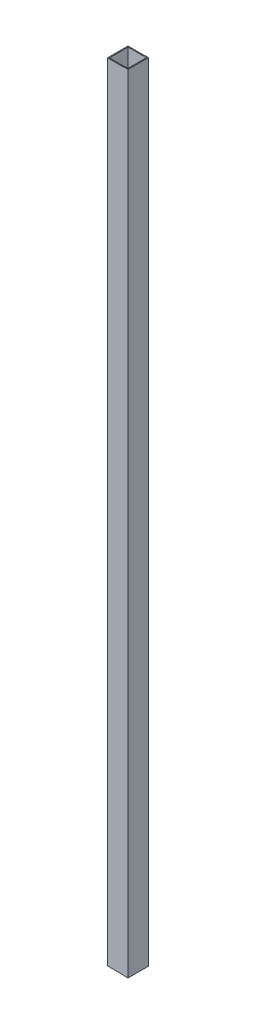
SolidWorks part; units mm, degrees
ref_plane "Front Plane" through (0, 0, 0) normal (0, 0, 1) x (1, 0, 0)
ref_plane "Top Plane" through (0, 0, 0) normal (0, 1, 0) x (1, 0, 0)
ref_plane "Right Plane" through (0, 0, 0) normal (1, 0, 0) x (0, 0, -1)
sketch "Sketch1" plane through (0, 0, 0) normal (0, 1, 0) x (1, 0, 0)
  line L0 (0, 0) -> (0, 50)
  line L1 (0, 50) -> (50, 50)
  line L2 (50, 50) -> (50, 0)
  line L3 (50, 0) -> (0, 0)
  line L4 (2.2, 47.8) -> (47.8, 47.8)
  line L5 (47.8, 47.8) -> (47.8, 2.2)
  line L6 (47.8, 2.2) -> (2.2, 2.2)
  line L7 (2.2, 2.2) -> (2.2, 47.8)
  dimension "D1" = 50
  dimension "D2" = 50
  dimension "D3" = 2.2
extrude "Boss-Extrude1" add sketch "Sketch1" along normal blind 1923
sketch "Sketch2" plane through (0, 0, 0) normal (0, 0, 1) x (1, 0, 0)
  line L0 (0, 0) -> (0, 0.5)
  line L1 (0, 1923) -> (0, 0) construction
  line L2 (0, 0.5) -> (40, 0.5)
  line L3 (40, 0.5) -> (40, 0)
  line L5 (40, 0) -> (0, 0)
  line L6 (0, 1923) -> (40, 1923)
  line L7 (0, 1923) -> (50, 1923) construction
  line L8 (40, 1923) -> (40, 1922.5)
  line L9 (40, 1922.5) -> (0, 1922.5)
  line L10 (0, 1922.5) -> (0, 1923)
  dimension "D1" = 0.5
  dimension "D2" = 40
  dimension "D3" = 0.5
  dimension "D4" = 40
extrude "Cut-Extrude2" cut sketch "Sketch2" against normal blind 50
equation "\"SquareTube_length\"=1923.0"
equation "\"D1@Boss-Extrude1\"=\"SquareTube_length\""
equation "\"SquareTube_inBack1_cutDepth50_R\"=50"
equation "\"D1@Sketch2\"= \"SquareTube_inBack6_cutDepth50_R\""
equation "\"SquareTube_inBack1_cutDepth50_L\"=50"
equation "\"D3@Sketch2\" = \"SquareTube_inBack6_cutDepth50_L\""
equation "\"CarBeamWidth\"=700.0"
equation "\"MetalSheet_3mm_length\"=5030.0"
equation "\"MetalSheet_3mm_width\"=1923.0"
equation "\"MetalSheet_3mm_FloorCut_L_length\"=1764.0"
equation "\"MetalSheet_3mm_FloorCut_L_disdance\"=1665.0"
equation "\"MetalSheet_3mm_FloorCut_R_length\"=1764.0"
equation "\"MetalSheet_3mm_FloorCut_R_disdance\"=1665.0"
equation "\"indoorHeight\"=1940.0"
equation "\"x\"=66.0"
equation "\"da\"=62.0"
equation "\"SquareTube_wheel_length\"= 750"
equation "\"channelSteel_length\"=5030.0"
equation "\"SquareTube_inFront1_cutDepth50_R\"=0.5"
equation "\"SquareTube_inFront1_cutDepth50_L\"=0.5"
equation "\"SquareTube_inFront2_cutDepth50_R\"=0.5"
equation "\"SquareTube_inFront2_cutDepth50_L\"=0.5"
equation "\"SquareTube_inFront3_cutDepth50_R\"=0.5"
equation "\"SquareTube_inFront3_cutDepth50_L\"=0.5"
equation "\"SquareTube_inFront4_cutDepth50_R\"=0.5"
equation "\"SquareTube_inFront4_cutDepth50_L\"=0.5"
equation "\"SquareTube_inFront5_cutDepth50_R\"=50"
equation "\"SquareTube_inFront5_cutDepth50_L\"=50"
equation "\"SquareTube_inFront6_cutDepth50_R\"=50"
equation "\"SquareTube_inFront6_cutDepth50_L\"=50"
equation "\"SquareTube_inFront7_cutDepth50_R\"=50"
equation "\"SquareTube_inFront7_cutDepth50_L\"=50"
equation "\"SquareTube_inFront8_cutDepth50_R\"=50"
equation "\"SquareTube_inFront8_cutDepth50_L\"=50"
equation "\"SquareTube_inFront9_cutDepth50_R\"=50"
equation "\"SquareTube_inFront9_cutDepth50_L\"=50"
equation "\"SquareTube_inFront10_cutDepth50_R\"=50"
equation "\"SquareTube_inFront10_cutDepth50_L\"=50"
equation "\"SquareTube_inBack2_cutDepth50_R\"=50"
equation "\"SquareTube_inBack2_cutDepth50_L\"=50"
equation "\"SquareTube_inBack3_cutDepth50_R\"=50"
equation "\"SquareTube_inBack3_cutDepth50_L\"=50"
equation "\"SquareTube_inBack4_cutDepth50_R\"=50"
equation "\"SquareTube_inBack4_cutDepth50_L\"=50"
equation "\"SquareTube_inBack5_cutDepth50_R\"=50"
equation "\"SquareTube_inBack5_cutDepth50_L\"=50"
equation "\"SquareTube_inBack6_cutDepth50_R\"=0.5"
equation "\"SquareTube_inBack6_cutDepth50_L\"=0.5"
equation "\"SquareTube_inFront11_cutDepth50_R\"=50"
equation "\"SquareTube_inFront11_cutDepth50_L\"=50"
equation "\"SquareTube_inFront12_cutDepth50_R\"=50"
equation "\"SquareTube_inFront12_cutDepth50_L\"=50"
equation "\"SquareTube_inFront13_cutDepth50_R\"=50"
equation "\"SquareTube_inFront13_cutDepth50_L\"=50"
equation "\"SquareTube_inFront14_cutDepth50_R\"=50"
equation "\"SquareTube_inFront14_cutDepth50_L\"=50"
equation "\"SquareTube_inBack7_cutDepth50_R\"=0.5"
equation "\"SquareTube_inBack7_cutDepth50_L\"=0.5"
equation "\"SquareTube_inBack8_cutDepth50_R\"=0.5"
equation "\"SquareTube_inBack8_cutDepth50_L\"=0.5"
